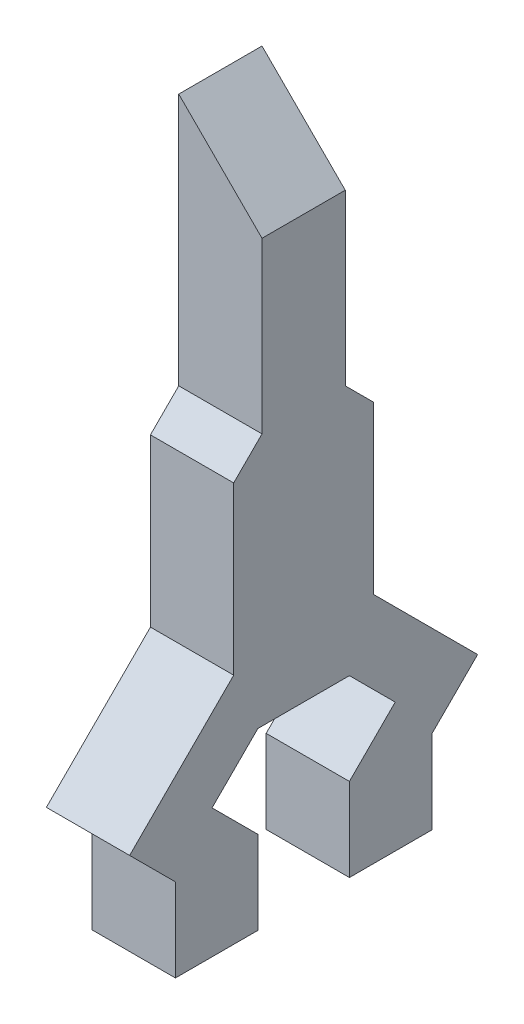
SolidWorks part; units mm, degrees
ref_plane "Front Plane" through (0, 0, 0) normal (0, 0, 1) x (1, 0, 0)
ref_plane "Top Plane" through (0, 0, 0) normal (0, 1, 0) x (1, 0, 0)
ref_plane "Right Plane" through (0, 0, 0) normal (1, 0, 0) x (0, 0, -1)
sketch "Sketch1" plane through (0, 0, 0) normal (1, 0, 0) x (0, 0, -1)
  line L0 (5.5, 5.5) -> (11, 0)
  line L1 (-5.5, 5.5) -> (5.5, 5.5)
  line L2 (-5.5, 5.5) -> (-5.5, -5.5) construction
  line L3 (-5.5, -5.5) -> (5.5, -5.5) construction
  line L4 (5.5, 5.5) -> (5.5, -5.5) construction
  line L5 (-5.5, 5.5) -> (5.5, -5.5) construction
  line L6 (-5.5, -5.5) -> (5.5, 5.5) construction
  line L7 (11, 0) -> (5.5, -5.5)
  line L8 (-5.5, 5.5) -> (-11, 0)
  line L9 (-11, 0) -> (-5.5, -5.5)
  line L10 (-20.8995, 0) -> (-15.3995, -5.5)
  line L11 (-8.3995, 12.5) -> (-20.8995, 0)
  line L12 (-8.3995, 12.5) -> (8.3995, 12.5) construction
  line L13 (8.3995, 12.5) -> (20.8995, 0)
  line L14 (20.8995, 0) -> (15.3995, -5.5)
  line L17 (-20.8995, 0) -> (-10.4497, -10.4497) construction
  line L18 (20.8995, 0) -> (10.4497, -10.4497) construction
  line L19 (-8.3995, 12.5) -> (-8.3995, 32.5)
  line L20 (-8.3995, 32.5) -> (0, 40.8995)
  line L21 (0, 40.8995) -> (8.3995, 32.5)
  line L22 (8.3995, 32.5) -> (8.3995, 12.5)
  line L23 (5.5, -5.5) -> (5.5, -15.5)
  line L24 (-5.5, -5.5) -> (-5.5, -15.5)
  line L25 (-5.5, -15.5) -> (-15.3995, -15.5)
  line L26 (-15.3995, -15.5) -> (-15.3995, -5.5)
  line L27 (15.3995, -5.5) -> (15.3995, -15.5)
  line L28 (15.3995, -15.5) -> (5.5, -15.5)
  point P0 (0, 0)
  dimension "D1" = 11
  dimension "D2" = 7
  dimension "D3" = 20
  dimension "D4" = 10
extrude "Boss-Extrude1" add sketch "Sketch1" along normal blind 10
sketch "Sketch2" plane through (0, 0, 0) normal (0, 0, 1) x (1, 0, 0)
  line L0 (0, 6.25) -> (0, 66.25)
  line L1 (0, 12.5) -> (0, 0) construction
  line L2 (0, 66.25) -> (10, 56.25)
  line L3 (10, 56.25) -> (10, 6.25)
  line L4 (10, 12.5) -> (10, 0) construction
  line L5 (10, 6.25) -> (0, 6.25)
  dimension "D1" = 60
  dimension "D2" = 45
extrude "Boss-Extrude2" add sketch "Sketch2" along normal mid plane 10
